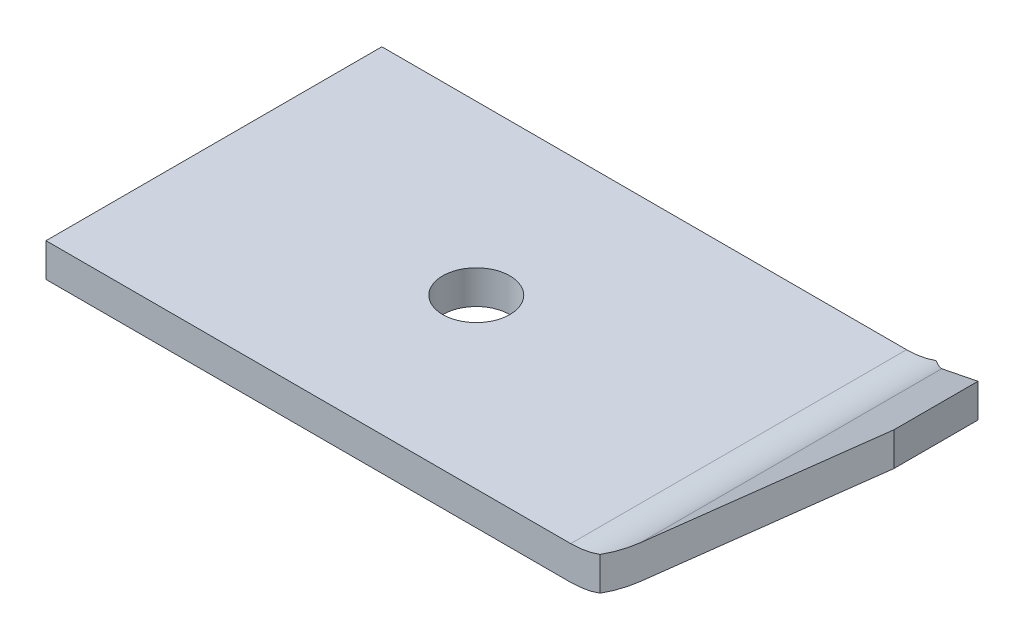
SolidWorks part; units mm, degrees
ref_plane "Front Plane" through (0, 0, 0) normal (0, 0, 1) x (1, 0, 0)
ref_plane "Top Plane" through (0, 0, 0) normal (0, 1, 0) x (1, 0, 0)
ref_plane "Right Plane" through (0, 0, 0) normal (1, 0, 0) x (0, 0, -1)
sketch "Sketch2" plane through (0, 0, 0) normal (0, 1, 0) x (1, 0, 0)
  line L0 (16.5, 10) -> (21.5, 6.25)
  line L1 (0, 0) -> (21.5, 0) construction
  line L2 (0, 0) -> (0, 10)
  line L3 (0, 10) -> (21.5, 10) construction
  line L4 (21.5, 0) -> (21.5, 10) construction
  line L5 (21.5, 6.25) -> (21.5, 3.75)
  line L6 (21.5, 3.75) -> (16.5, 0)
  line L7 (16.5, 0) -> (0, 0)
  line L8 (0, 10) -> (16.5, 10)
  dimension "D1" = 21.5
  dimension "D2" = 10
  dimension "D3" = 16.5
  dimension "D4" = 2.5
extrude "Boss-Extrude1" add sketch "Sketch2" along normal blind 5
sketch "Sketch8" plane through (0, 0, 0) normal (0, 0, 1) x (1, 0, 0)
  line L0 (0, 0) -> (0, 1)
  line L1 (0, 5) -> (0, 0) construction
  line L2 (0, 1) -> (15.623, 1)
  line L3 (16.5, 5) -> (16.5, 0) construction
  line L4 (17.1848, 1.5478) -> (21.5, 5)
  line L5 (21.5, 5) -> (21.5, 4)
  line L6 (21.5, 5) -> (21.5, 0) construction
  line L7 (21.5, 4) -> (17.1848, 0.5478)
  line L8 (15.623, 0) -> (0, 0)
  line L10 (-3.4908, 9.0899) -> (24.6477, 9.0899)
  line L11 (-3.4908, 9.0899) -> (-3.4908, -3.7783)
  line L12 (-3.4908, -3.7783) -> (24.6477, -3.7783)
  line L13 (24.6477, 9.0899) -> (24.6477, -3.7783)
  arc A0 (17.1848, 0.5478) -> (15.623, 0) centre (15.623, 2.5) cw
  arc A1 (15.623, 1) -> (17.1848, 1.5478) centre (15.623, 3.5) ccw
  point P17 (16.5, 0)
  point P20 (16.5, 1)
  dimension "D3" = 2.5
  dimension "D1" = 1
  dimension "D2" = 1
extrude "Cut-Extrude5" cut sketch "Sketch8" against normal blind 10
sketch "Sketch9" plane through (0, 1, 0) normal (0, 1, 0) x (1, 0, 0)
  line L0 (7.8115, 0) -> (7.8115, 5) construction
  line L1 (15.623, 0) -> (0, 0) construction
  circle A0 centre (7.8115, 5) radius 1
  dimension "D2" = 2
  dimension "D1" = 5
extrude "Cut-Extrude6" cut sketch "Sketch9" against normal blind 1
